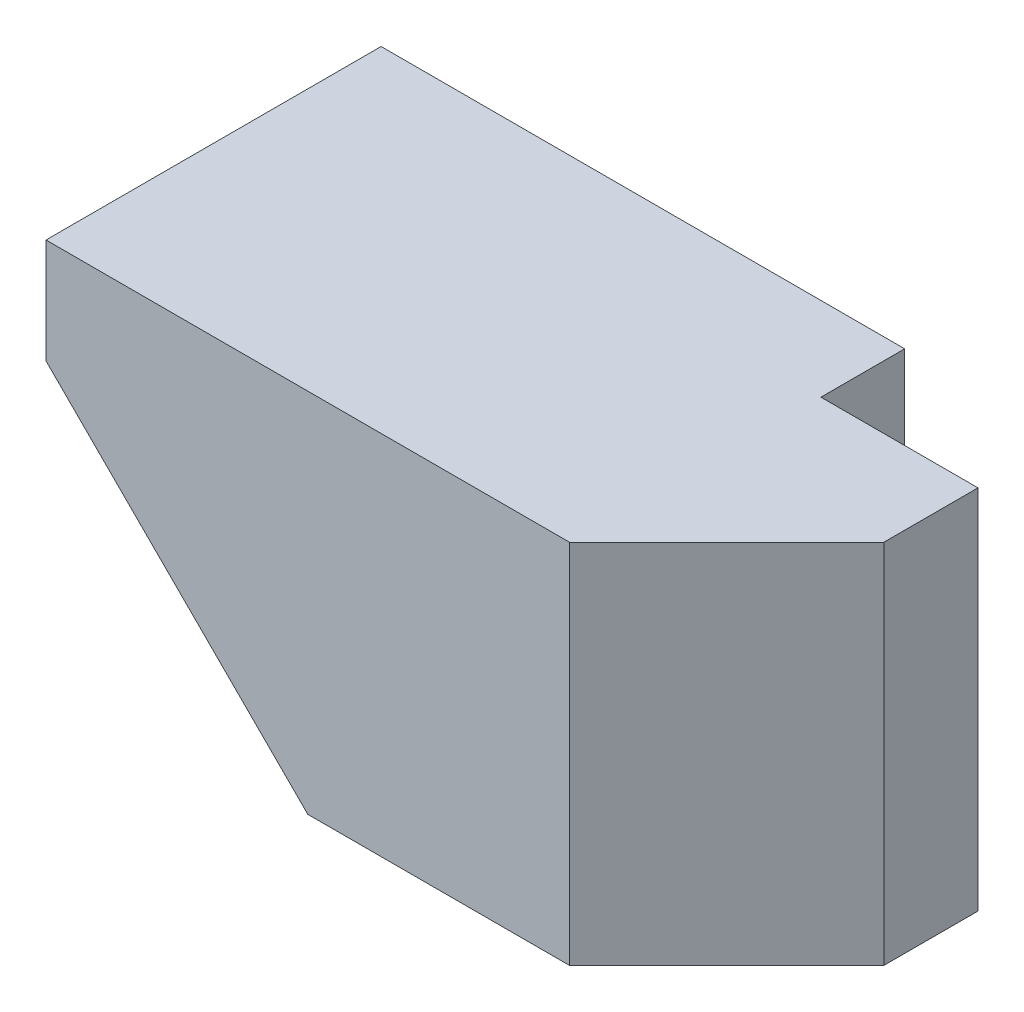
SolidWorks part; units mm, degrees
material "Zoltek Panex 33"
ref_plane "Front Plane" through (0, 0, 0) normal (0, 0, 1) x (1, 0, 0)
ref_plane "Top Plane" through (0, 0, 0) normal (0, 1, 0) x (1, 0, 0)
ref_plane "Right Plane" through (0, 0, 0) normal (1, 0, 0) x (0, 0, -1)
sketch "Sketch1" plane through (0, 0, 0) normal (0, 0, 1) x (1, 0, 0)
  line L0 (-27.0726, 20.2671) -> (-27.0726, -14.7329)
  line L1 (-27.0726, -14.7329) -> (37.9274, -14.7329)
  line L2 (37.9274, -14.7329) -> (37.9274, 20.2671)
  line L3 (37.9274, 20.2671) -> (-27.0726, 20.2671)
  dimension "D1" = 35
  dimension "D2" = 65
  dimension "D3" = 37.9274
  dimension "D4" = 20.2671
extrude "Boss-Extrude1" add sketch "Sketch1" along normal blind 12
sketch "Sketch2" plane through (0, 0, 0) normal (0, 0, -1) x (-1, 0, 0)
  line L0 (-37.9274, -14.7329) -> (-22.9274, -14.7329)
  line L1 (27.0726, -14.7329) -> (-37.9274, -14.7329) construction
  line L2 (-22.9274, -14.7329) -> (-22.9274, 20.2671)
  line L3 (-37.9274, 20.2671) -> (27.0726, 20.2671) construction
  line L4 (-22.9274, 20.2671) -> (-37.9274, 20.2671)
  line L5 (-37.9274, 20.2671) -> (-37.9274, -14.7329)
  dimension "D1" = 15
extrude "Cut-Extrude1" cut sketch "Sketch2" against normal blind 8
sketch "Sketch3" plane through (0, 0, 12) normal (0, 0, 1) x (1, 0, 0)
  line L0 (-27.0726, 20.2671) -> (-27.0726, 10.2671)
  line L1 (-27.0726, 20.2671) -> (-27.0726, -14.7329) construction
  line L2 (-27.0726, 10.2671) -> (-2.0726, -14.7329)
  line L3 (-27.0726, -14.7329) -> (37.9274, -14.7329) construction
  line L4 (-2.0726, -14.7329) -> (37.9274, -14.7329)
  line L5 (37.9274, -14.7329) -> (37.9274, 20.2671)
  line L6 (37.9274, 20.2671) -> (-27.0726, 20.2671)
  dimension "D1" = 10
  dimension "D2" = 25
extrude "Boss-Extrude3" add sketch "Sketch3" along normal blind 20
sketch "Sketch4" plane through (0, -14.7329, 0) normal (0, -1, 0) x (1, 0, 0)
  line L0 (37.9274, 32) -> (22.9274, 32)
  line L1 (-2.0726, 32) -> (37.9274, 32) construction
  line L2 (22.9274, 32) -> (37.9274, 17)
  line L3 (37.9274, 32) -> (37.9274, 8) construction
  line L4 (37.9274, 17) -> (37.9274, 32)
  dimension "D1" = 15
  dimension "D2" = 15
extrude "Cut-Extrude2" cut sketch "Sketch4" against normal blind 41
